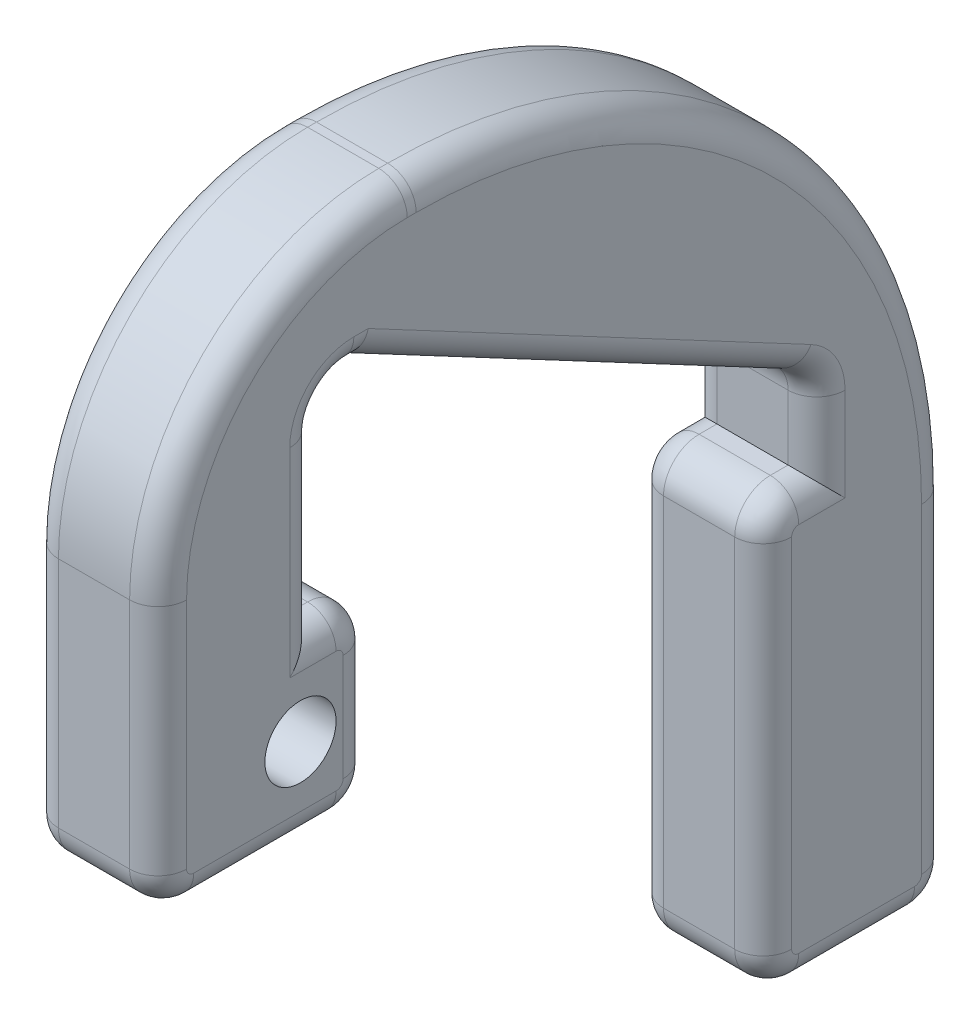
SolidWorks part; units mm, degrees
ref_plane "Front Plane" through (0, 0, 0) normal (0, 0, 1) x (1, 0, 0)
ref_plane "Top Plane" through (0, 0, 0) normal (0, 1, 0) x (1, 0, 0)
ref_plane "Right Plane" through (0, 0, 0) normal (1, 0, 0) x (0, 0, -1)
sketch "Sketch1" plane through (0, 0, 0) normal (1, 0, 0) x (0, 0, -1)
  line L0 (-5.715, 23.0176) -> (-5.715, 4.5391)
  line L1 (-5.715, 4.5391) -> (1.905, 4.5391)
  line L2 (0, 18.2551) -> (1.5313, 18.2551)
  line L3 (17.78, 9.6231) -> (17.78, 6.5457)
  line L4 (15.875, 6.5457) -> (15.875, 14.7245) construction
  line L5 (1.5313, 18.2551) -> (17.78, 9.6231)
  line L6 (-5.715, 23.0176) -> (22.5425, 23.0176)
  line L7 (22.5425, 23.0176) -> (22.5425, -8.7324)
  line L8 (22.5425, -8.7324) -> (15.875, -8.7324)
  line L9 (15.875, -8.7324) -> (15.875, 6.5457)
  line L10 (15.875, 6.5457) -> (17.78, 6.5457)
  line L13 (0, 18.2551) -> (0, 10.8891)
  line L14 (0, 10.8891) -> (1.905, 10.8891)
  line L15 (1.905, 10.8891) -> (1.905, 4.5391)
  circle A0 centre (-0.635, 7.7141) radius 1.27
  point P4 (15.875, 10.6351)
  dimension "D12" = 2.54
  dimension "D2" = 4.7625
  dimension "D3" = 7.62
  dimension "D4" = 1.905
  dimension "D5" = 2.54
  dimension "D6" = 4.7625
  dimension "D7" = 31.75
  dimension "D8" = 13.716
  dimension "D9" = 6.35
  dimension "D10" = 13.97
  dimension "D11" = 3.175
  dimension "D14" = 7.62
extrude "Boss-Extrude1" add sketch "Sketch1" along normal blind 4.572
fillet "Fillet4" radius 1.27 4 edges at (2.286, 6.5457, -15.875) (2.286, 10.8891, -1.905) (2.286, 4.5391, -1.905) (2.286, 4.5391, 5.715)
fillet "Fillet5" radius 1.27 4 edges at (2.286, -8.7324, -22.5425) (2.286, -8.7324, -15.875) (2.286, 18.2551, 0) (2.286, 9.6231, -17.78)
fillet "Fillet6" radius 8.89 1 edges at (2.286, 23.0176, 5.715)
fillet "Fillet7" radius 19.05 1 edges at (2.286, 23.0176, -22.5425)
fillet "Fillet8" radius 1.016 46 edges at (0, 20.4138, 3.1112) (0, 9.9684, 5.715) (0, 4.9111, 5.343) (0, 4.5391, 1.905) (0, 4.9111, -1.533) (0, 7.7141, -1.905) (0, 10.5172, -1.533) (0, 10.8891, -0.3175) (0, 13.9371, 0) (0, 7.7027, -17.78) (0, 6.5457, -17.4625) (0, 6.1738, -16.247) (0, -1.0933, -15.875) (0, -8.3604, -16.247) (0, -8.7324, -19.2088) (0, -8.3604, -22.1705) (0, -1.7474, -22.5425) (0, 17.438, -16.9629) (0, 23.0176, -3.3338) (4.572, -8.3604, -22.1705) (4.572, -8.7324, -19.2088) (4.572, -8.3604, -16.247) (4.572, -1.0933, -15.875) (4.572, 6.1738, -16.247) (4.572, 6.5457, -17.4625) (4.572, 7.7027, -17.78) (4.572, 13.9371, 0) (4.572, 10.8891, -0.3175) (4.572, 10.5172, -1.533) (4.572, 7.7141, -1.905) (4.572, 4.9111, -1.533) (4.572, 4.5391, 1.905) (4.572, 4.9111, 5.343) (4.572, 9.9684, 5.715) (4.572, 20.4138, 3.1112) (4.572, 23.0176, -3.3338) (4.572, 17.438, -16.9629) (4.572, -1.7474, -22.5425) (0, 18.2551, -1.4006) (0, 17.8832, -0.372) (0, 9.514, -17.5985) (4.572, 18.2551, -1.4006) (4.572, 17.8832, -0.372) (4.572, 9.514, -17.5985) (0, 14.1182, -9.3185) (4.572, 14.1182, -9.3185)
